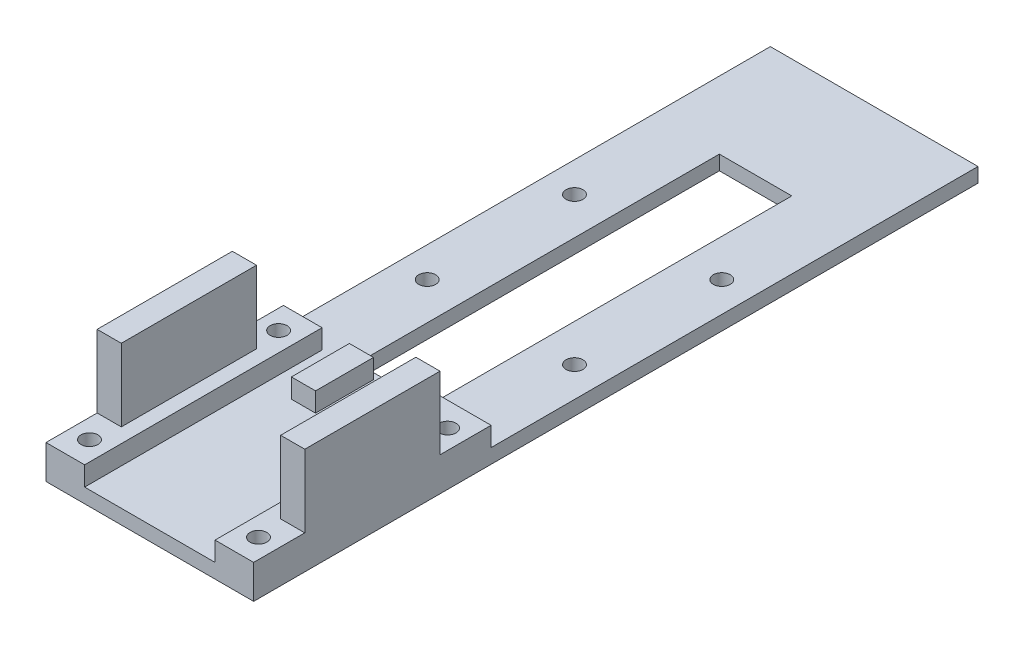
SolidWorks part; units mm, degrees
material "ABS"
ref_plane "Front Plane" through (0, 0, 0) normal (0, 0, 1) x (1, 0, 0)
ref_plane "Top Plane" through (0, 0, 0) normal (0, 1, 0) x (1, 0, 0)
ref_plane "Right Plane" through (0, 0, 0) normal (1, 0, 0) x (0, 0, -1)
sketch "Sketch1" plane through (0, 0, 0) normal (0, 1, 0) x (1, 0, 0)
  line L1 (21.5, -75) -> (-21.5, -75)
  line L2 (21.5, -75) -> (21.5, 75)
  line L3 (21.5, 75) -> (-21.5, 75)
  line L4 (-21.5, -75) -> (-21.5, 75)
  line L5 (21.5, -75) -> (-21.5, 75) construction
  line L6 (21.5, 75) -> (-21.5, -75) construction
  point P0 (0, 0)
  dimension "D1" = 150
  dimension "D2" = 43
extrude "Boss-Extrude1" add sketch "Sketch1" along normal blind 3
sketch "Sketch2" plane through (0, 3, 0) normal (0, 1, 0) x (1, 0, 0)
  line L0 (0, 75) -> (0, 38.94) construction
  line L1 (21.5, 75) -> (-21.5, 75) construction
  line L2 (0, 75) -> (15.25, 75) construction
  line L3 (15.25, 75) -> (15.25, 28.19) construction
  line L5 (15.25, 28.19) -> (-15.25, 28.19) construction
  line L6 (15.25, 28.19) -> (15.25, -2.31) construction
  line L7 (15.25, -2.31) -> (-15.25, -2.31) construction
  line L8 (-15.25, 28.19) -> (-15.25, -2.31) construction
  circle A0 centre (15.25, 28.19) radius 1.75
  circle A1 centre (-15.25, 28.19) radius 1.75
  circle A2 centre (-15.25, -2.31) radius 1.75
  circle A3 centre (15.25, -2.31) radius 1.75
  dimension "D6" = 3.5
  dimension "D7" = 3.5
  dimension "D8" = 3.5
  dimension "D9" = 3.5
  dimension "D1" = 36.06
  dimension "D2" = 15.25
  dimension "D3" = 46.81
  dimension "D4" = 30.5
  dimension "D5" = 30.5
extrude "Cut-Extrude1" cut sketch "Sketch2" against normal blind 10
sketch "Sketch3" plane through (0, 3, 0) normal (0, 1, 0) x (1, 0, 0)
  line L0 (-15.25, 28.19) -> (15.25, -2.31) construction
  line L1 (-15.25, 28.19) -> (15.25, 28.19) construction
  line L2 (-15.25, 28.19) -> (-15.25, -2.31) construction
  line L3 (-15.25, -2.31) -> (15.25, -2.31) construction
  line L4 (15.25, 28.19) -> (15.25, -2.31) construction
  line L6 (7.5, 50.44) -> (-7.5, 50.44)
  line L7 (7.5, 50.44) -> (7.5, -24.56)
  line L8 (7.5, -24.56) -> (-7.5, -24.56)
  line L9 (-7.5, 50.44) -> (-7.5, -24.56)
  line L10 (7.5, 50.44) -> (-7.5, -24.56) construction
  line L11 (7.5, -24.56) -> (-7.5, 50.44) construction
  point P6 (0, 12.94)
  dimension "D1" = 75
  dimension "D2" = 15
extrude "Cut-Extrude2" cut sketch "Sketch3" against normal blind 10
sketch "Sketch4" plane through (0, 3, 0) normal (0, 1, 0) x (1, 0, 0)
  line L0 (0, -24.56) -> (2.65, -24.56) construction
  line L1 (-7.5, -24.56) -> (7.5, -24.56) construction
  line L2 (2.65, -24.56) -> (2.65, -25.83) construction
  line L3 (8.15, -25.83) -> (-2.85, -25.83) construction
  line L4 (8.15, -37.83) -> (-2.85, -37.83) construction
  line L5 (-2.85, -25.83) -> (-7.85, -25.83)
  line L6 (-2.85, -25.83) -> (-2.85, -37.83)
  line L7 (-2.85, -37.83) -> (-7.85, -37.83)
  line L8 (-7.85, -25.83) -> (-7.85, -37.83)
  line L9 (8.15, -25.83) -> (13.15, -25.83)
  line L10 (8.15, -25.83) -> (8.15, -37.83)
  line L11 (8.15, -37.83) -> (13.15, -37.83)
  line L12 (13.15, -25.83) -> (13.15, -37.83)
  line L14 (2.65, -37.83) -> (6.7668, -37.83)
  line L15 (2.65, -37.83) -> (2.65, -36.33)
  line L16 (2.65, -36.33) -> (6.7668, -36.33)
  line L17 (6.7668, -37.83) -> (6.7668, -36.33)
  line L18 (2.65, -37.83) -> (6.7668, -37.83)
  line L19 (2.65, -37.83) -> (2.65, -41.33)
  line L20 (2.65, -41.33) -> (6.7668, -41.33)
  line L21 (6.7668, -37.83) -> (6.7668, -41.33)
  point P8 (2.65, -25.83)
  dimension "D1" = 2.65
  dimension "D2" = 1.27
  dimension "D3" = 11
  dimension "D4" = 5
  dimension "D5" = 5
  dimension "D6" = 12
  dimension "D7" = 12
  dimension "D8" = 1.5
  dimension "D9" = 3.5
extrude "Boss-Extrude2" add sketch "Sketch4" along normal blind 4 contours L6 L5 L8 L7 | L10 L9 L12 L11 | L19 L18 L21 L20 | L15 L14 L17 L16
sketch "Sketch5" plane through (0, 3, 0) normal (0, 1, 0) x (1, 0, 0)
  line L0 (-7.85, -25.83) -> (-21.5, -25.83) construction
  line L1 (-21.5, 75) -> (-21.5, -75) construction
  line L2 (13.15, -25.83) -> (21.5, -25.83) construction
  line L3 (21.5, -75) -> (21.5, 75) construction
  line L4 (-21.5, -75) -> (21.5, -75) construction
  line L5 (-21.5, -25.83) -> (-13.5, -25.83)
  line L6 (-21.5, -25.83) -> (-21.5, -75)
  line L7 (-21.5, -75) -> (-13.5, -75)
  line L8 (-13.5, -25.83) -> (-13.5, -75)
  line L10 (21.5, -25.83) -> (13.5, -25.83)
  line L11 (21.5, -25.83) -> (21.5, -75)
  line L12 (21.5, -75) -> (13.5, -75)
  line L13 (13.5, -25.83) -> (13.5, -75)
  dimension "D1" = 8
  dimension "D2" = 8
extrude "Boss-Extrude3" add sketch "Sketch5" along normal blind 4
sketch "Sketch7" plane through (0, 3, 0) normal (0, 1, 0) x (1, 0, 0)
  line L1 (13.15, -37.83) -> (13.5, -37.83)
  line L2 (13.15, -37.83) -> (13.15, -25.83)
  line L3 (13.15, -25.83) -> (13.5, -25.83)
  line L4 (13.5, -37.83) -> (13.5, -25.83)
extrude "Boss-Extrude4" add sketch "Sketch7" along normal blind 4
sketch "Sketch8" plane through (0, 7, 0) normal (0, 1, 0) x (1, 0, 0)
  line L0 (21.5, -75) -> (17.5, -75) construction
  line L1 (13.5, -75) -> (21.5, -75) construction
  line L2 (17.5, -75) -> (17.5, -70) construction
  line L3 (21.5, -25.83) -> (-21.5, -25.83) construction
  line L4 (0, -25.83) -> (0, -75) construction
  line L5 (-13.5, -75) -> (13.5, -75) construction
  line L6 (21.5, -50.415) -> (-21.5, -50.415) construction
  line L7 (21.5, -75) -> (21.5, -25.83) construction
  line L8 (-21.5, -25.83) -> (-21.5, -75) construction
  circle A0 centre (17.5, -70) radius 1.75
  circle A1 centre (17.5, -30.83) radius 1.75
  circle A2 centre (-17.5, -70) radius 1.75
  circle A3 centre (-17.5, -30.83) radius 1.75
  dimension "D2" = 3.5
  dimension "D1" = 5
extrude "Cut-Extrude3" cut sketch "Sketch8" against normal through all
sketch "Sketch9" plane through (0, 7, 0) normal (0, 1, 0) x (1, 0, 0)
  line L0 (21.5, -75) -> (21.5, -64.41) construction
  line L1 (21.5, -75) -> (21.5, -25.83) construction
  line L2 (0, -75) -> (0, -24.56) construction
  line L3 (21.5, -64.41) -> (16.5, -64.41)
  line L4 (21.5, -64.41) -> (21.5, -36.41)
  line L5 (21.5, -36.41) -> (16.5, -36.41)
  line L6 (16.5, -64.41) -> (16.5, -36.41)
  line L7 (-13.5, -75) -> (13.5, -75) construction
  line L8 (-7.5, -24.56) -> (7.5, -24.56) construction
  line L9 (-21.5, -36.41) -> (-16.5, -36.41)
  line L10 (-16.5, -64.41) -> (-16.5, -36.41)
  line L11 (-21.5, -64.41) -> (-16.5, -64.41)
  line L12 (-21.5, -64.41) -> (-21.5, -36.41)
  dimension "D1" = 10.59
  dimension "D2" = 5
  dimension "D3" = 28
extrude "Boss-Extrude5" add sketch "Sketch9" along normal blind 15
sketch "Sketch10" plane through (0, 0, 0) normal (0, -1, 0) x (1, 0, 0)
  circle A0 centre (-17.5, 70) radius 3
  circle A1 centre (-17.5, 30.83) radius 3
  circle A2 centre (17.5, 30.83) radius 3
  circle A3 centre (17.5, 70) radius 3
  dimension "D1" = 6
  dimension "D2" = 6
  dimension "D3" = 6
  dimension "D4" = 6
extrude "Cut-Extrude5" cut sketch "Sketch10" against normal blind 2
